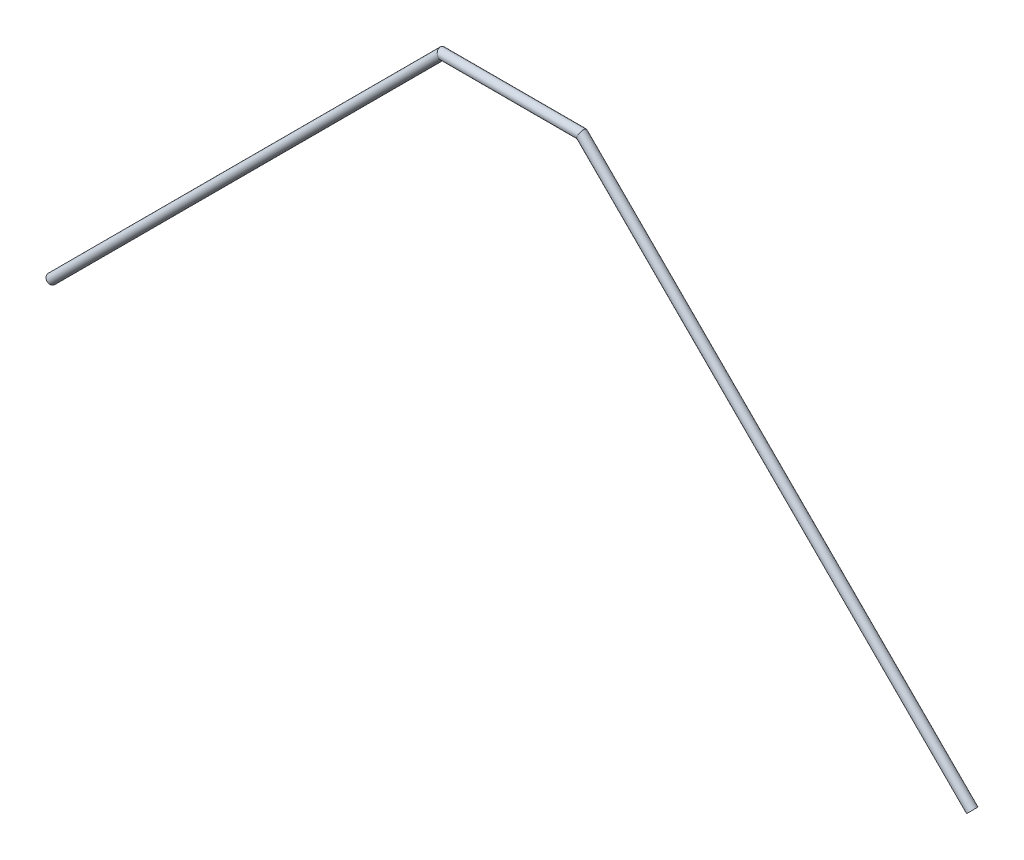
SolidWorks part; units mm, degrees
material "6061 Alloy"
ref_plane "Front" through (0, 0, 0) normal (0, 0, 1) x (1, 0, 0)
ref_plane "Top" through (0, 0, 0) normal (0, 1, 0) x (1, 0, 0)
ref_plane "Right" through (0, 0, 0) normal (1, 0, 0) x (0, 0, -1)
sketch "Sketch1" plane through (0, 0, 0) normal (0, 0, 1) x (1, 0, 0)
  line L0 (-381, 0) -> (381, 0)
  line L1 (-381, 0) -> (-2514.6, -2133.6)
  line L2 (381, 0) -> (2514.6, -2133.6)
  line L3 (-2514.6, -2133.6) -> (2514.6, -2133.6) construction
  point P4 (0, 0)
  dimension "D1" = 762
  dimension "D2" = 2133.6
  dimension "D3" = 45
sketch "Sketch2" plane through (0, 0, 0) normal (1, 0, 0) x (0, 0, -1)
  circle A0 centre (0, 0) radius 25.4
  dimension "D1" = 50.8
sweep "Sweep1" add profiles "Sketch2" path "Sketch1"
ref_plane "Plane1" through (0, -2133.6, 0) normal (0, 1, 0) x (1, 0, 0)
